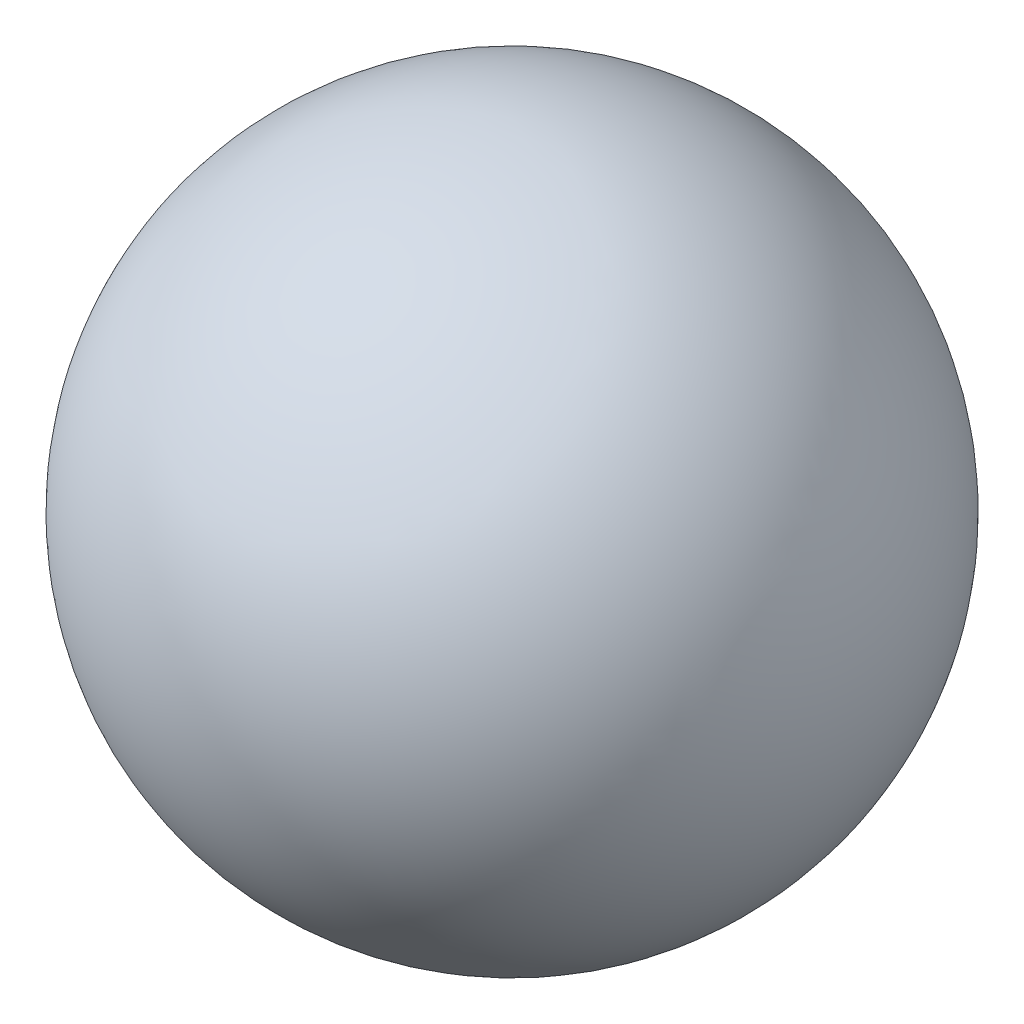
SolidWorks part; units mm, degrees
ref_plane "前视基准面" through (0, 0, 0) normal (0, 0, 1) x (1, 0, 0)
ref_plane "上视基准面" through (0, 0, 0) normal (0, 1, 0) x (1, 0, 0)
ref_plane "右视基准面" through (0, 0, 0) normal (1, 0, 0) x (0, 0, -1)
other "Configuration Table"
sketch "草图1" plane through (0, 0, 0) normal (0, 0, 1) x (1, 0, 0)
  line L0 (0, 0) -> (9, 0) construction
  line L1 (0, 0) -> (-44.9894, 0) construction
  line L2 (9, 0) -> (-9, 0)
  arc A0 (9, 0) -> (-9, 0) centre (0, 0) ccw
  dimension "D1" = 9
revolve "旋转6" add sketch "草图1" angle 360 about L2
